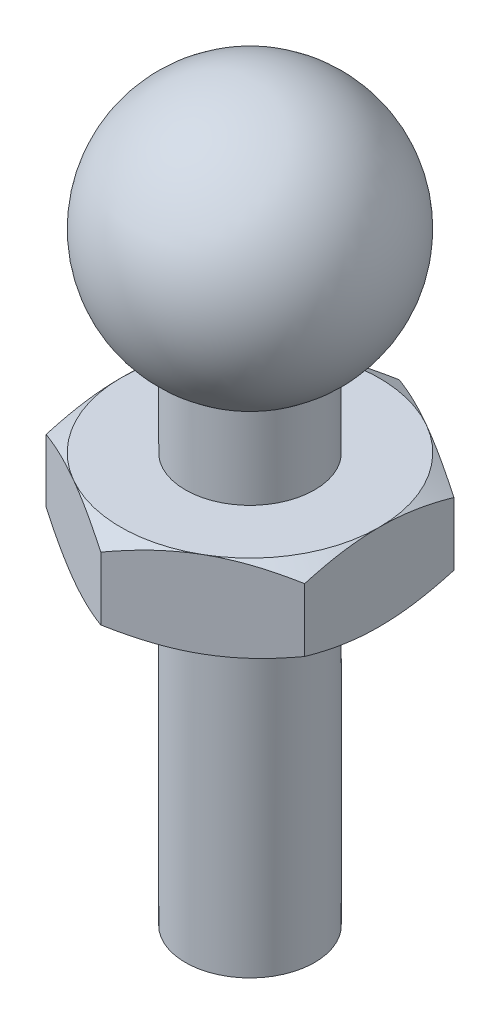
SolidWorks part; units mm, degrees
ref_plane "Front Plane" through (0, 0, 0) normal (0, 0, 1) x (1, 0, 0)
ref_plane "Top Plane" through (0, 0, 0) normal (0, 1, 0) x (1, 0, 0)
ref_plane "Right Plane" through (0, 0, 0) normal (1, 0, 0) x (0, 0, -1)
sketch "Sketch1" plane through (0, 0, 0) normal (0, 0, 1) x (1, 0, 0)
  line L0 (0, 0) -> (0, 14)
  line L1 (0, 0) -> (1.5, 0)
  line L2 (1.5, 0) -> (1.5, 11.4019)
  line L3 (0, 14) -> (0, 17)
  line L4 (0, 0) -> (0, 21.9734) construction
  arc A0 (0, 11) -> (0, 17) centre (0, 14) ccw
  dimension "D1" = 3
  dimension "D2" = 11
  dimension "D3" = 1.5
revolve "Revolve1" add sketch "Sketch1" angle 360 about L4
sketch "Sketch2" plane through (0, 0, 0) normal (0, 0, 1) x (1, 0, 0)
  line L0 (-4.0878, 7.5) -> (4.0878, 7.5)
  point P2 (0, 7.5)
  dimension "D1" = 7.5
split line "Split Line1"
ref_plane "Plane1" through (0, 7.5, 0) normal (0, 1, 0) x (1, 0, 0)
sketch "Sketch3" plane through (0, 7.5, 0) normal (0, 1, 0) x (1, 0, 0)
  line L1 (0, -3.4641) -> (3, -1.7321)
  line L2 (3, -1.7321) -> (3, 1.7321)
  line L3 (3, 1.7321) -> (0, 3.4641)
  line L4 (0, 3.4641) -> (-3, 1.7321)
  line L5 (-3, 1.7321) -> (-3, -1.7321)
  line L6 (-3, -1.7321) -> (0, -3.4641)
  circle A0 centre (0, 0) radius 1.5
  circle A1 centre (0, 0) radius 3 construction
  circle A2 centre (0, 0) radius 1.5 construction
  dimension "D1" = 6
extrude "Boss-Extrude1" add sketch "Sketch3" along normal blind 2
sketch "Sketch4" plane through (0, 7.5, 0) normal (0, -1, 0) x (1, 0, 0)
  circle A0 centre (0, 0) radius 3
  circle A1 centre (0, 0) radius 4.5206
extrude "Cut-Extrude5" cut sketch "Sketch4" against normal blind 10 draft 60
sketch "Sketch5" plane through (0, 9.5, 0) normal (0, 1, 0) x (1, 0, 0)
  circle A2 centre (0, 0) radius 4.4464
  circle A3 centre (0, 0) radius 3
extrude "Cut-Extrude8" cut sketch "Sketch5" against normal blind 2 draft 60
scale "Scale1" scale about centroid uniform scaling yes scale factor 18
